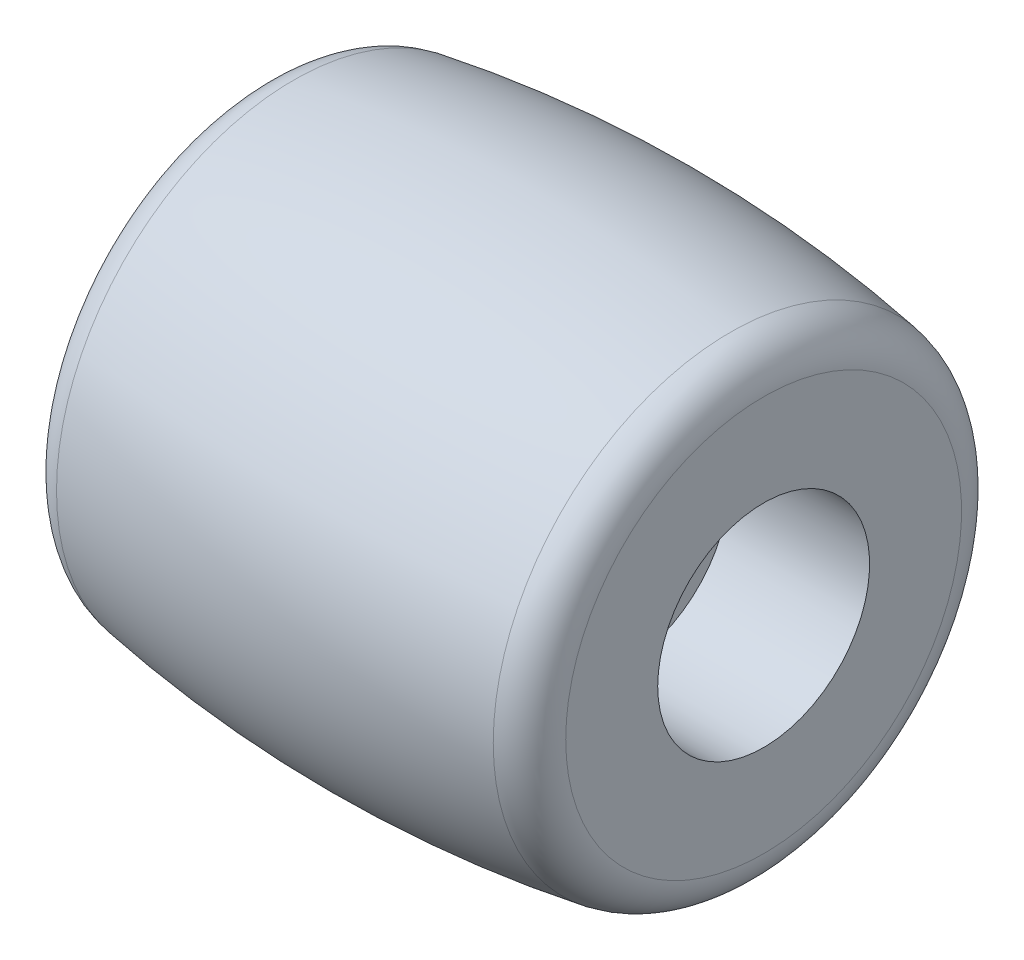
SolidWorks part; units mm, degrees
material "天然ｺﾞﾑ"
ref_plane "正面" through (0, 0, 0) normal (0, 0, 1) x (1, 0, 0)
ref_plane "平面" through (0, 0, 0) normal (0, 1, 0) x (1, 0, 0)
ref_plane "右側面" through (0, 0, 0) normal (1, 0, 0) x (0, 0, -1)
sketch "ｽｹｯﾁ1" plane through (0, 0, 0) normal (0, 0, 1) x (1, 0, 0)
  line L0 (0, 0) -> (12131.0927, 0) construction
  line L1 (4.2, 2.5) -> (-4.2, 2.5)
  line L2 (-4.2, 2.5) -> (-4.2, 4)
  line L3 (-4.2, 4) -> (-9.5, 4)
  line L4 (-9.5, 4) -> (-9.5, 8.7288)
  line L5 (4.2, 2.5) -> (4.2, 4)
  line L6 (4.2, 4) -> (9.5, 4)
  line L7 (9.5, 4) -> (9.5, 8.7288)
  line L8 (0, 0) -> (0, 9.625) construction
  arc A0 (-9.5, 8.7288) -> (9.5, 8.7288) centre (0, -41.175) cw
  point P6 (0, 2.5)
  point P8 (-4.3468, 6.7466)
  point P16 (9.5, 9.0446)
  point P17 (9.5, 5.2736)
  dimension "D3" = 50.8
  dimension "D1" = 19
  dimension "D2" = 19.25
  dimension "D4" = 8
  dimension "D5" = 5
  dimension "D6" = 5.3
revolve "回転1" add sketch "ｽｹｯﾁ1" angle 360 about L0
fillet "ﾌｨﾚｯﾄ1" radius 1.5 2 edges at (9.5, 0, 8.7288) (-9.5, 0, 8.7288)
